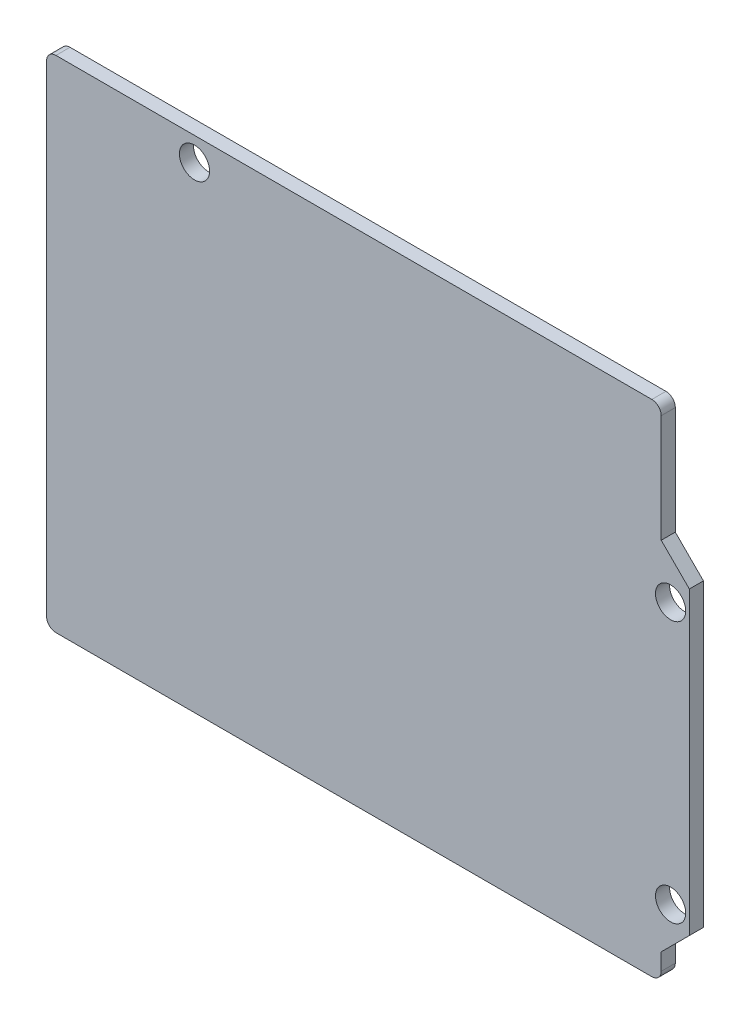
SolidWorks part; units mm, degrees
ref_plane "Plan de face" through (0, 0, 0) normal (0, 0, 1) x (1, 0, 0)
ref_plane "Plan de dessus" through (0, 0, 0) normal (0, 1, 0) x (1, 0, 0)
ref_plane "Plan de droite" through (0, 0, 0) normal (1, 0, 0) x (0, 0, -1)
sketch "Esquisse1" plane through (0, 0, 0) normal (0, 0, 1) x (1, 0, 0)
  line L0 (-55.8128, 0) -> (56.1089, 0) construction
  line L1 (0, -35.6788) -> (0, 37.7514) construction
  line L2 (31.265, 25.65) -> (31.265, 14.15)
  line L3 (-33.265, 26.65) -> (30.265, 26.65)
  line L4 (-34.265, 25.65) -> (-34.265, -25.65)
  line L5 (-33.265, -26.65) -> (30.265, -26.65)
  line L6 (34.265, 11.15) -> (34.265, -20.85)
  line L7 (31.265, 14.15) -> (34.265, 11.15)
  line L8 (34.265, -20.85) -> (31.265, -23.85)
  line L9 (31.265, -23.85) -> (31.265, -25.65)
  arc A0 (-34.265, -25.65) -> (-33.265, -26.65) centre (-33.265, -25.65) ccw
  arc A1 (-33.265, 26.65) -> (-34.265, 25.65) centre (-33.265, 25.65) ccw
  arc A2 (31.265, 25.65) -> (30.265, 26.65) centre (30.265, 25.65) ccw
  arc A3 (31.265, -25.65) -> (30.265, -26.65) centre (30.265, -25.65) cw
  circle A4 centre (32.265, 8.92) radius 1.61
  circle A5 centre (32.265, -18.98) radius 1.61
  circle A6 centre (-18.495, 24.15) radius 1.61
  point P21 (31.265, -26.65)
  dimension "D9" = 1
  dimension "D10" = 3.22
  dimension "D11" = 3.22
  dimension "D15" = 3.22
  dimension "D1" = 53.3
  dimension "D2" = 68.53
  dimension "D3" = 27.9
  dimension "D4" = 3
  dimension "D5" = 135
  dimension "D6" = 12.5
  dimension "D7" = 3
  dimension "D8" = 135
  dimension "D12" = 15.23
  dimension "D13" = 32
  dimension "D14" = 50.76
  dimension "D16" = 2.5
  dimension "D17" = 2
  dimension "D18" = 2
extrude "Boss.-Extru.1" add sketch "Esquisse1" along normal blind 1.5
